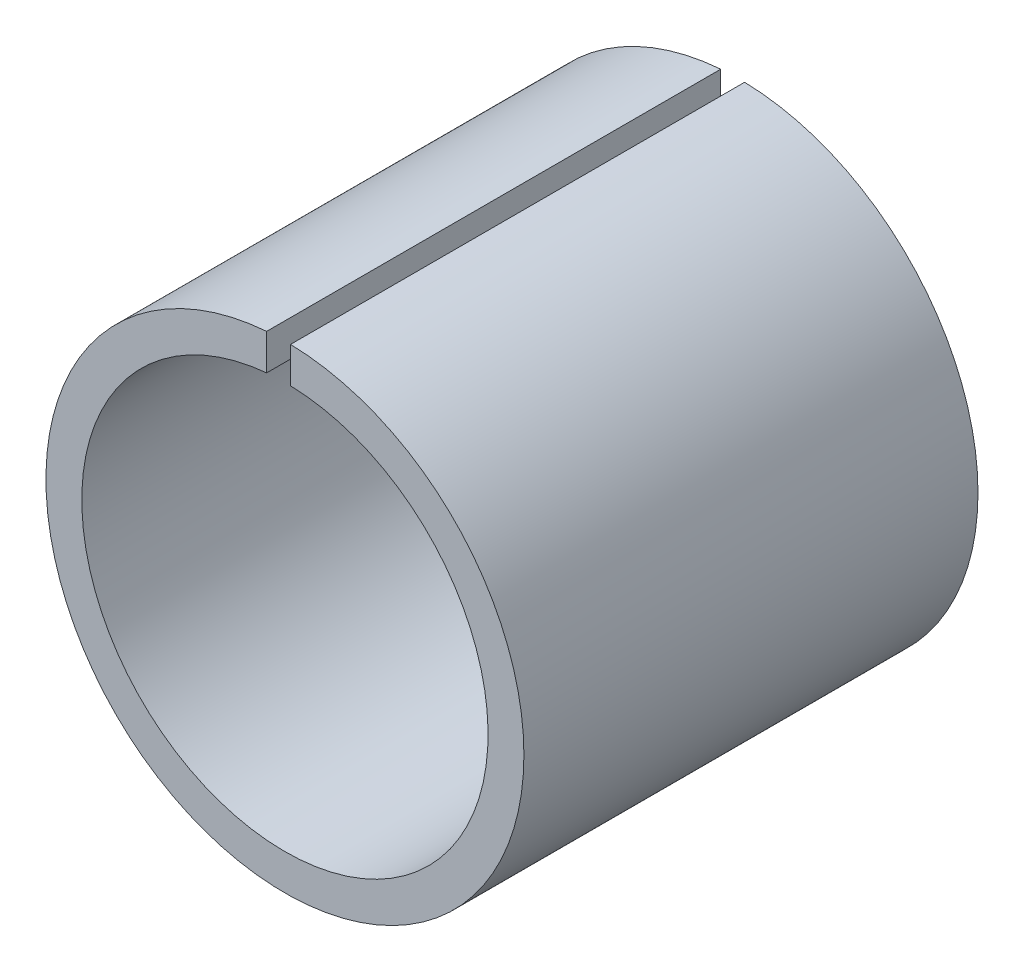
SolidWorks part; units mm, degrees
material "AISI 1020"
ref_plane "Front" through (0, 0, 0) normal (0, 0, 1) x (1, 0, 0)
ref_plane "Top" through (0, 0, 0) normal (0, 1, 0) x (1, 0, 0)
ref_plane "Right" through (0, 0, 0) normal (1, 0, 0) x (0, 0, -1)
sketch "Sketch1" plane through (0, 0, 0) normal (0, 0, 1) x (1, 0, 0)
  circle A0 centre (0, 0) radius 10
  dimension "D1" = 20
extrude "Boss-Extrude1" add sketch "Sketch1" along normal blind 19
sketch "Sketch3" plane through (0, 0, 19) normal (0, 0, 1) x (1, 0, 0)
  circle A0 centre (0, 0) radius 8.5
  dimension "D1" = 17
extrude "Cut-Extrude1" cut sketch "Sketch3" against normal blind 19
ref_plane "Plane2" through (0, 8, 0) normal (0, 1, 0) x (1, 0, 0)
sketch "Sketch4" plane through (0, 8, 0) normal (0, 1, 0) x (1, 0, 0)
  line L0 (-0.7653, 0) -> (0.2347, 0)
  line L1 (8.5, 0) -> (-8.5, 0) construction
  line L2 (10, 0) -> (-10, 0) construction
  line L3 (0.2347, 0) -> (0.2347, -19)
  line L4 (-10, -19) -> (10, -19) construction
  line L5 (0.2347, -19) -> (-0.7653, -19)
  line L6 (-0.7653, -19) -> (-0.7653, 0)
  dimension "D1" = 1
extrude "Cut-Extrude3" cut sketch "Sketch4" along normal blind 3
